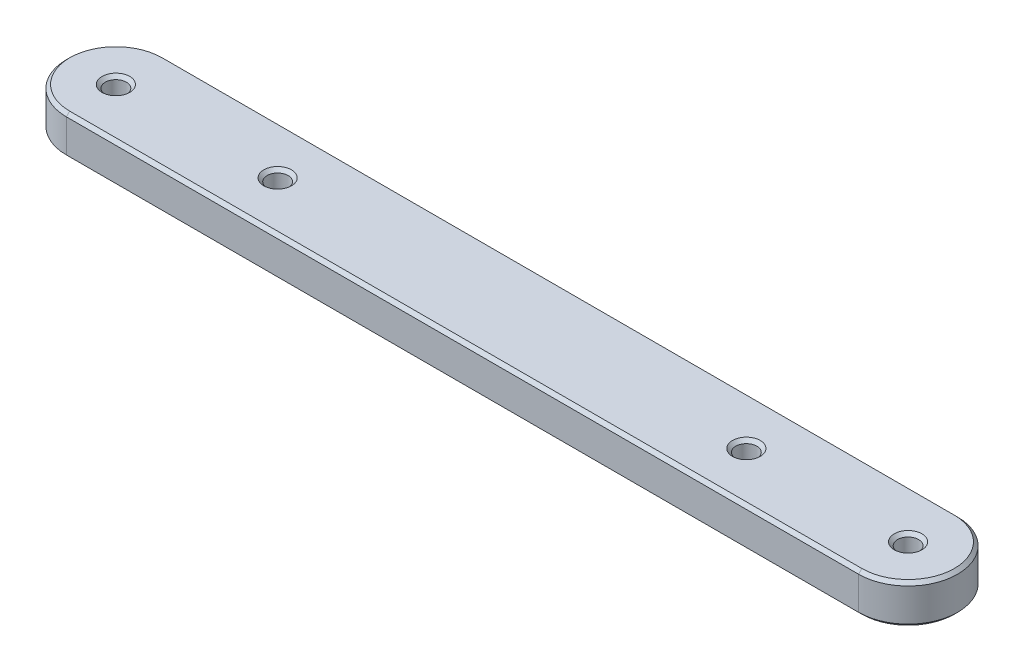
SolidWorks part; units mm, degrees
ref_plane "Front Plane" through (0, 0, 0) normal (0, 0, 1) x (1, 0, 0)
ref_plane "Top Plane" through (0, 0, 0) normal (0, 1, 0) x (1, 0, 0)
ref_plane "Right Plane" through (0, 0, 0) normal (1, 0, 0) x (0, 0, -1)
sketch "Sketch1" plane through (0, 0, 0) normal (0, 1, 0) x (1, 0, 0)
  line L0 (0, 0) -> (120, 0) construction
  line L1 (0, 0) -> (120, 0) construction
  line L2 (0, 7.5) -> (120, 7.5)
  line L3 (0, -7.5) -> (120, -7.5)
  line L4 (60, 0) -> (60, -7.5) construction
  circle A0 centre (0, 0) radius 1.6
  circle A1 centre (120, 0) radius 1.6
  arc A2 (0, 7.5) -> (0, -7.5) centre (0, 0) ccw
  arc A3 (120, -7.5) -> (120, 7.5) centre (120, 0) ccw
  circle A4 centre (24.5, 0) radius 1.6
  circle A5 centre (95.5, 0) radius 1.6
  point P5 (60, 0)
  dimension "D2" = 3.2
  dimension "D1" = 120
  dimension "D3" = 15
  dimension "D4" = 24.5
extrude "Boss-Extrude1" add sketch "Sketch1" along normal mid plane 6 contours L3 A3 L2 A2 A0 A1
chamfer "Chamfer1" distance 0.5 angle 45 16 edges at (127.5, -3, 0) (60, -3, -7.5) (-7.5, -3, 0) (60, -3, 7.5) (120, -3, 1.6) (0, -3, 1.6) (24.5, -3, 1.6) (95.5, -3, 1.6) (-7.5, 3, 0) (60, 3, -7.5) (127.5, 3, 0) (60, 3, 7.5) (120, 3, 1.6) (0, 3, 1.6) (24.5, 3, 1.6) (95.5, 3, 1.6)
